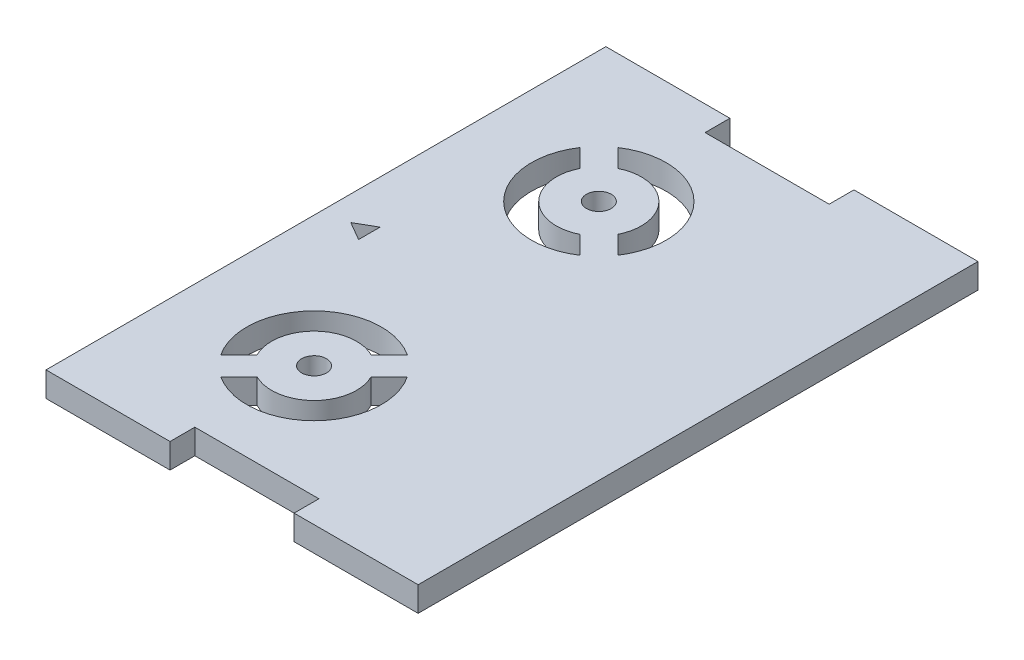
SolidWorks part; units mm, degrees
ref_plane "Plano frontal" through (0, 0, 0) normal (0, 0, 1) x (1, 0, 0)
ref_plane "Plano superior" through (0, 0, 0) normal (0, 1, 0) x (1, 0, 0)
ref_plane "Plano direito" through (0, 0, 0) normal (1, 0, 0) x (0, 0, -1)
sketch "Sketch1" plane through (0, 0, 0) normal (0, 1, 0) x (1, 0, 0)
  line L1 (22.5, -33.85) -> (-22.5, -33.85)
  line L2 (22.5, -33.85) -> (22.5, 33.85)
  line L3 (22.5, 33.85) -> (-22.5, 33.85)
  line L4 (-22.5, -33.85) -> (-22.5, 33.85)
  line L5 (22.5, -33.85) -> (-22.5, 33.85) construction
  line L6 (22.5, 33.85) -> (-22.5, -33.85) construction
  point P0 (0, 0)
  dimension "D1" = 67.7
  dimension "D2" = 45
extrude "Boss-Extrude1" add sketch "Sketch1" along normal mid plane 3
sketch "Sketch2" plane through (0, 0, 0) normal (0, 1, 0) x (1, 0, 0)
  line L0 (-22.5, -33.85) -> (22.5, -33.85) construction
  line L1 (-7.5, -33.85) -> (7.5, -33.85)
  line L2 (-7.5, -33.85) -> (-7.5, -30.85)
  line L3 (-7.5, -30.85) -> (7.5, -30.85)
  line L4 (7.5, -33.85) -> (7.5, -30.85)
  line L6 (-1.65, 0) -> (1.65, 0) construction
  line L7 (7.5, 33.85) -> (7.5, 30.85)
  line L8 (-7.5, 30.85) -> (7.5, 30.85)
  line L9 (-7.5, 33.85) -> (-7.5, 30.85)
  line L10 (-7.5, 33.85) -> (7.5, 33.85)
  point P6 (0, -30.85)
  dimension "D1" = 3
  dimension "D2" = 15
extrude "Cut-Extrude1" cut sketch "Sketch2" against normal through all both and the other way through all
sketch "Sketch3" plane through (0, 0, 0) normal (0, 1, 0) x (1, 0, 0)
  line L0 (-5.6569, -16.1569) -> (-7.7782, -18.2782) construction
  line L16 (-11.3137, -10.5) -> (0, -21.8137) construction
  line L17 (0, -21.8137) -> (-2.1213, -23.935) construction
  line L18 (-2.1213, -23.935) -> (-13.435, -12.6213) construction
  line L19 (-13.435, -12.6213) -> (-11.3137, -10.5) construction
  line L20 (-22.5, 33.85) -> (-22.5, -33.85) construction
  line L21 (-6.7175, 17.2175) -> (-5.6569, 18.2782) construction
  line L26 (-1.65, 0) -> (1.65, 0) construction
  line L27 (-13.435, 12.6213) -> (-11.3137, 10.5) construction
  line L28 (-2.1213, 23.935) -> (-13.435, 12.6213) construction
  line L29 (0, 21.8137) -> (-2.1213, 23.935) construction
  line L30 (-11.3137, 10.5) -> (0, 21.8137) construction
  line L31 (-5.6569, 16.1569) -> (-7.7782, 18.2782) construction
  line L32 (0.0725, 12.7292) -> (-2.1196, 14.9213)
  line L33 (-6.7175, 17.2175) -> (-7.7782, 16.1569) construction
  line L34 (-2.2292, 10.4275) -> (-4.4213, 12.6196)
  line L35 (-9.0137, 21.8154) -> (-11.2058, 24.0076)
  line L36 (-11.3154, 19.5137) -> (-13.5076, 21.7058)
  line L37 (0.0725, -12.7292) -> (-2.1196, -14.9213)
  line L38 (-2.2292, -10.4275) -> (-4.4213, -12.6196)
  line L39 (-11.3154, -19.5137) -> (-13.5076, -21.7058)
  line L40 (-9.0137, -21.8154) -> (-11.2058, -24.0076)
  line L41 (-7.7782, 16.1569) -> (-10.3516, 13.5834) construction
  line L42 (-10.3516, 13.5834) -> (-12.4729, 11.4621) construction
  circle A0 centre (-6.7175, -17.2175) radius 1.5
  circle A1 centre (-6.7175, 17.2175) radius 1.5
  arc A2 (-13.5076, 21.7058) -> (-2.2292, 10.4275) centre (-6.7175, 17.2175) ccw
  arc A3 (-11.3154, 19.5137) -> (-4.4213, 12.6196) centre (-6.7175, 17.2175) ccw
  arc A4 (-2.1196, 14.9213) -> (-9.0137, 21.8154) centre (-6.7175, 17.2175) ccw
  circle A5 centre (-6.7175, 17.2175) radius 8.1394 construction
  circle A6 centre (-6.7175, 17.2175) radius 5.1394 construction
  arc A7 (0.0725, 12.7292) -> (-11.2058, 24.0076) centre (-6.7175, 17.2175) ccw
  arc A8 (-11.3154, -19.5137) -> (-4.4213, -12.6196) centre (-6.7175, -17.2175) cw
  arc A9 (-13.5076, -21.7058) -> (-2.2292, -10.4275) centre (-6.7175, -17.2175) cw
  arc A10 (-2.1196, -14.9213) -> (-9.0137, -21.8154) centre (-6.7175, -17.2175) cw
  arc A11 (0.0725, -12.7292) -> (-11.2058, -24.0076) centre (-6.7175, -17.2175) cw
  point P21 (-1.7154, 13.864)
  point P30 (0.9504, 16.1002)
  point P44 (-13.5076, -12.6196)
  dimension "D5" = 3
  dimension "D8" = 3.6394
  dimension "D1" = 3
  dimension "D2" = 16
  dimension "D3" = 45
  dimension "D4" = 10.5
  dimension "D7" = 3.1001
  dimension "D6" = 3
extrude "Cut-Extrude2" cut sketch "Sketch3" against normal through all both and the other way through all
sketch "Sketch4" plane through (0, 0, 0) normal (0, 1, 0) x (1, 0, 0)
  line L0 (-22.5, 33.85) -> (-22.5, -33.85) construction
  line L1 (-19.5, 0) -> (-17.25, -1.299)
  line L2 (-17.25, -1.299) -> (-17.25, 1.299)
  line L3 (-17.25, 1.299) -> (-19.5, 0)
  circle A0 centre (-18, 0) radius 1.5 construction
  dimension "D1" = 3
  dimension "D2" = 3
extrude "Cut-Extrude3" cut sketch "Sketch4" against normal through all both and the other way through all
